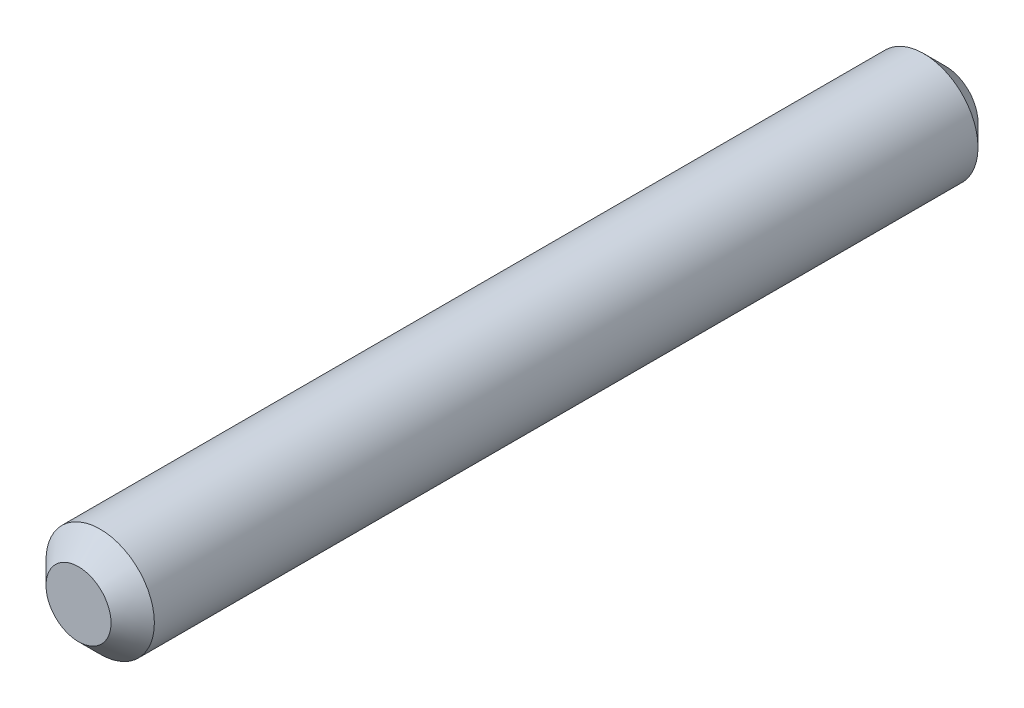
SolidWorks part; units mm, degrees
ref_plane "Front Plane" through (0, 0, 0) normal (0, 0, 1) x (1, 0, 0)
ref_plane "Top Plane" through (0, 0, 0) normal (0, 1, 0) x (1, 0, 0)
ref_plane "Right Plane" through (0, 0, 0) normal (1, 0, 0) x (0, 0, -1)
sketch "Sketch1" plane through (0, 0, 0) normal (0, 0, 1) x (1, 0, 0)
  circle A0 centre (0, 0) radius 2.5
  dimension "D1" = 5
extrude "Boss-Extrude1" add sketch "Sketch1" along normal blind 40
chamfer "Chamfer1" distance 1 angle 45 2 edges at (2.5, 0, 0) (2.5, 0, 40)
